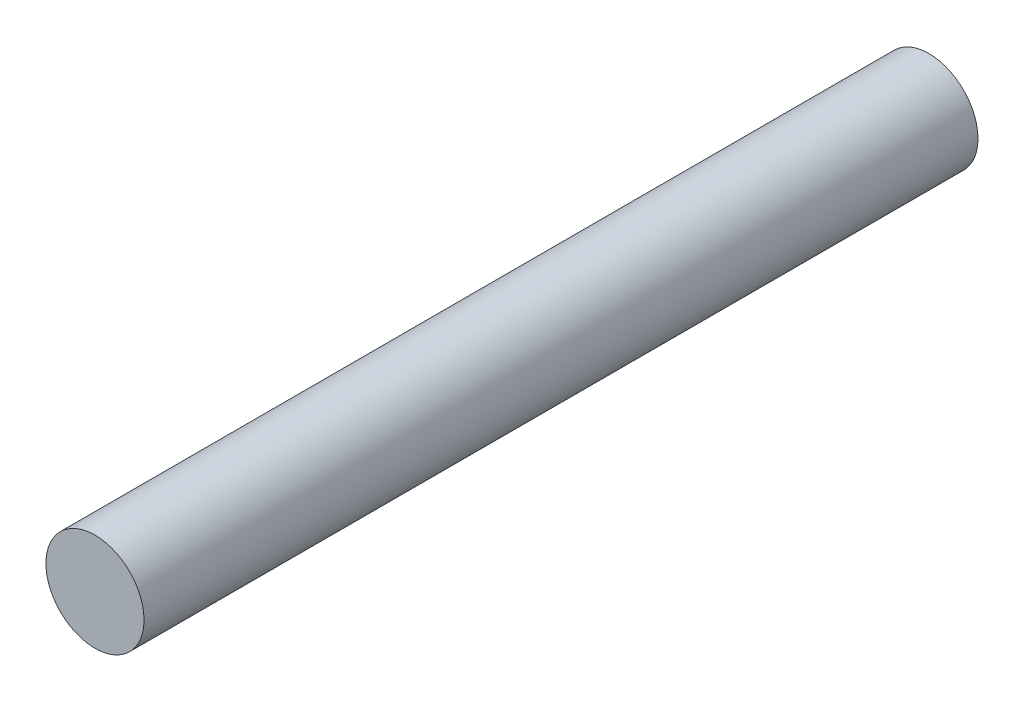
SolidWorks part; units mm, degrees
ref_plane "Piano frontale" through (0, 0, 0) normal (0, 0, 1) x (1, 0, 0)
ref_plane "Piano superiore" through (0, 0, 0) normal (0, 1, 0) x (1, 0, 0)
ref_plane "Piano destro" through (0, 0, 0) normal (1, 0, 0) x (0, 0, -1)
sketch "Schizzo1" plane through (0, 0, 0) normal (0, 0, 1) x (1, 0, 0)
  circle A0 centre (0, 0) radius 2
  dimension "D1" = 4
extrude "Estrusione-Estrusione1" add sketch "Schizzo1" along normal blind 34
